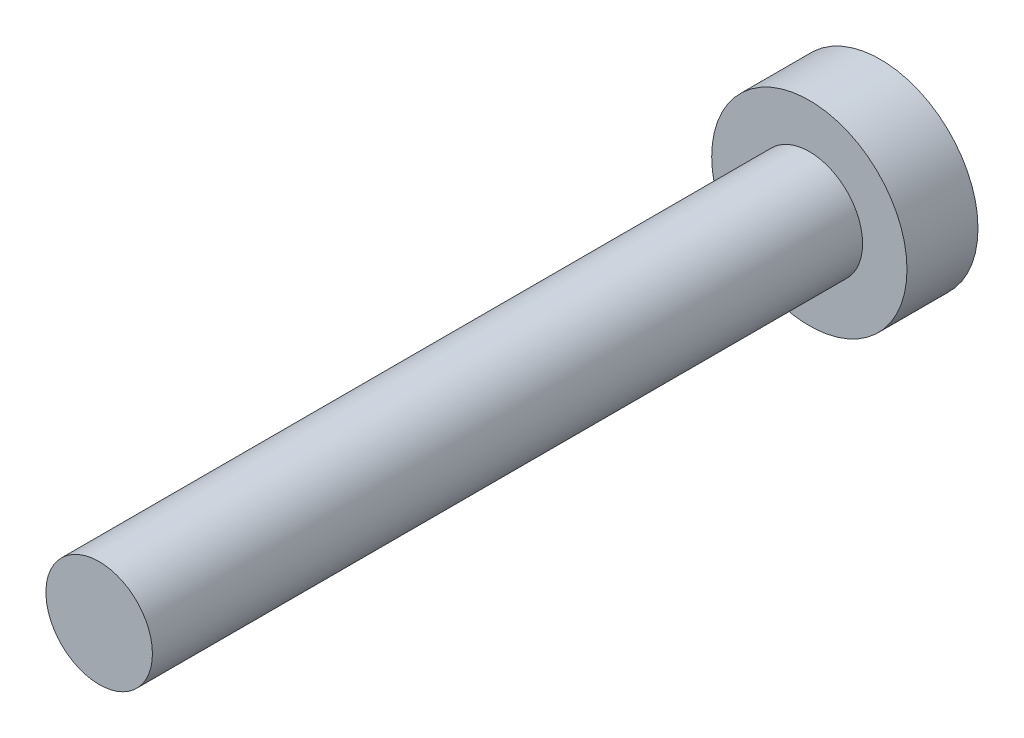
SolidWorks part; units mm, degrees
ref_plane "Plan de face" through (0, 0, 0) normal (0, 0, 1) x (1, 0, 0)
ref_plane "Plan de dessus" through (0, 0, 0) normal (0, 1, 0) x (1, 0, 0)
ref_plane "Plan de droite" through (0, 0, 0) normal (1, 0, 0) x (0, 0, -1)
sketch "Esquisse1" plane through (0, 0, 0) normal (0, 0, 1) x (1, 0, 0)
  circle A0 centre (0, 0) radius 2.75
  dimension "D1" = 5.5
extrude "Boss.-Extru.1" add sketch "Esquisse1" along normal blind 2
sketch "Esquisse2" plane through (0, 0, 2) normal (0, 0, 1) x (1, 0, 0)
  circle A0 centre (0, 0) radius 1.5
extrude "Boss.-Extru.2" add sketch "Esquisse2" along normal blind 20
